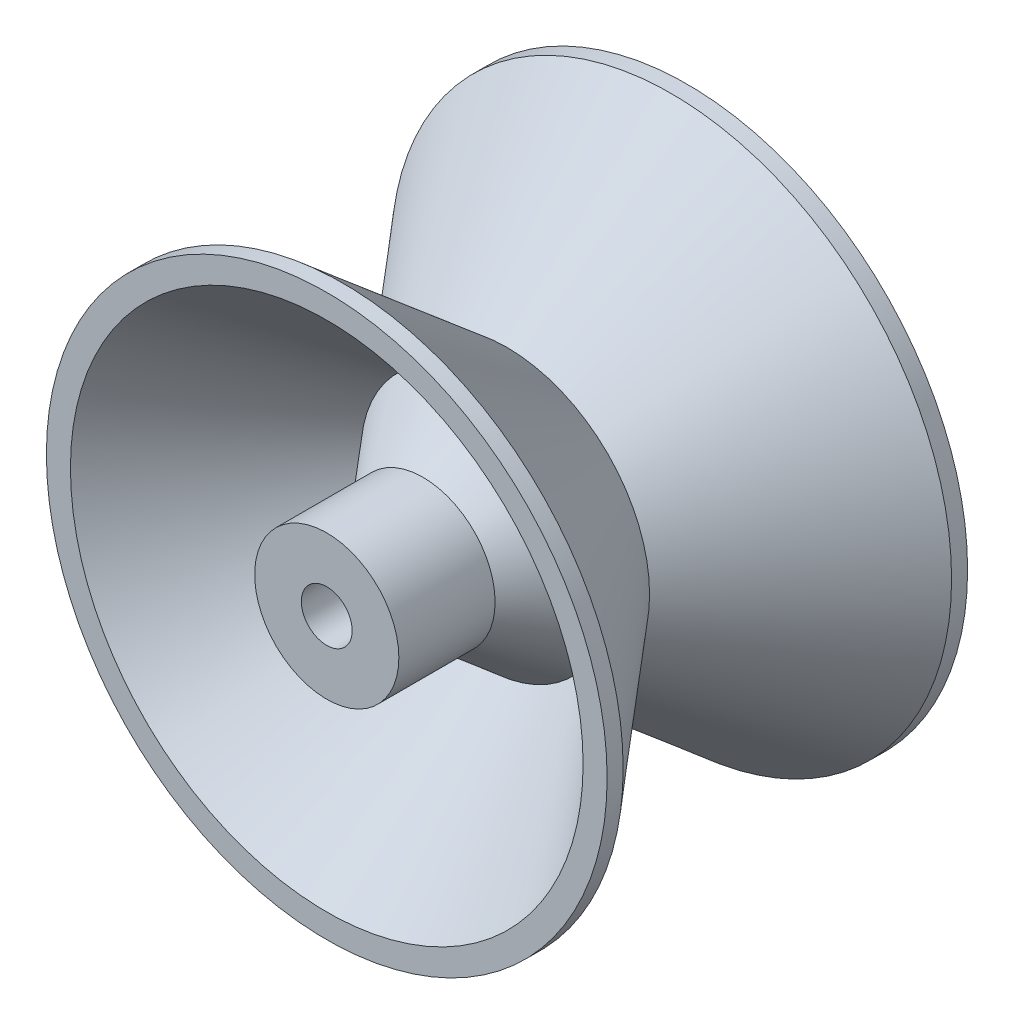
SolidWorks part; units mm, degrees
ref_plane "Front Plane" through (0, 0, 0) normal (0, 0, 1) x (1, 0, 0)
ref_plane "Top Plane" through (0, 0, 0) normal (0, 1, 0) x (1, 0, 0)
ref_plane "Right Plane" through (0, 0, 0) normal (1, 0, 0) x (0, 0, -1)
sketch "Sketch1" plane through (0, 0, 0) normal (0, 1, 0) x (1, 0, 0)
  line L0 (0, 0) -> (0, 60.9291) construction
  line L1 (3.175, 0) -> (3.175, 5)
  line L2 (5, 10.0141) -> (5, 34.9859)
  line L3 (3.175, 40) -> (3.175, 45)
  line L4 (3.175, 45) -> (9, 45)
  line L5 (35, 43) -> (35, 45)
  line L6 (35, 43) -> (17.7985, 22.5)
  line L7 (17.7985, 22.5) -> (35, 2)
  line L8 (35, 2) -> (35, 0)
  line L9 (35, 0) -> (32, 0)
  line L10 (3.175, 5) -> (5, 7.175) construction
  line L11 (9, 0) -> (9, 12.0144)
  line L12 (9, 32.9856) -> (15.4594, 25.2876)
  line L13 (15.4594, 19.7124) -> (32, 0)
  line L14 (9, 45) -> (9, 32.9856)
  line L15 (9, 12.0144) -> (15.4594, 19.7124)
  line L16 (15.4594, 25.2876) -> (32, 45)
  line L17 (32, 45) -> (35, 45)
  line L18 (9, 0) -> (3.175, 0)
  arc A0 (3.175, 5) -> (5, 10.0141) centre (-2.8006, 10.0141) ccw
  arc A1 (5, 34.9859) -> (3.175, 40) centre (-2.8006, 34.9859) ccw
  dimension "D2" = 5
  dimension "D1" = 40
  dimension "D3" = 6.35
  dimension "D4" = 70
  dimension "D5" = 45
  dimension "D6" = 2
  dimension "D7" = 10
  dimension "D8" = 4
  dimension "D9" = 3
  dimension "D10" = 80
revolve "Revolve1" add sketch "Sketch1" angle 360 about L0
